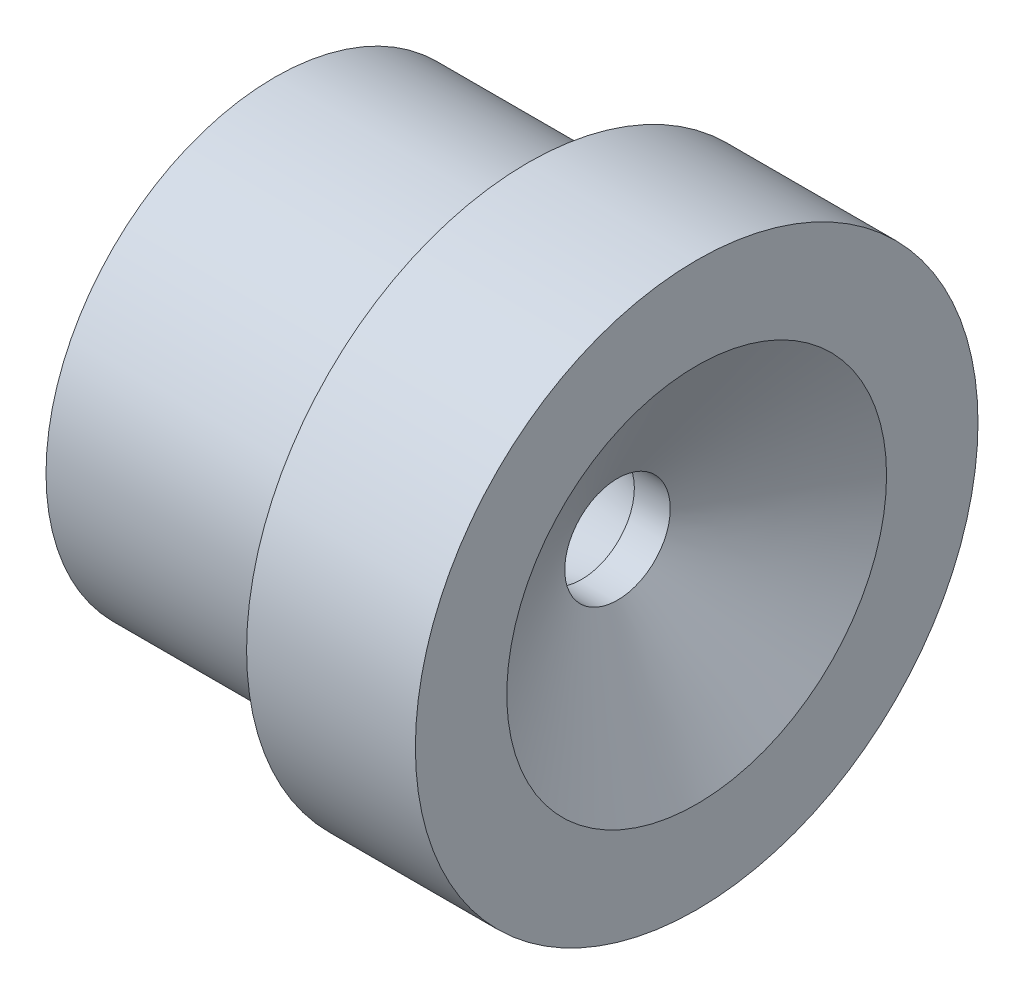
SolidWorks part; units mm, degrees
material "C (Graphite)"
ref_plane "Front Plane" through (0, 0, 0) normal (0, 0, 1) x (1, 0, 0)
ref_plane "Top Plane" through (0, 0, 0) normal (0, 1, 0) x (1, 0, 0)
ref_plane "Right Plane" through (0, 0, 0) normal (1, 0, 0) x (0, 0, -1)
sketch "Sketch1" plane through (0, 0, 0) normal (0, 1, 0) x (1, 0, 0)
  line L0 (0, 0) -> (0, 4.1275)
  line L1 (0, 4.1275) -> (-3.5745, 10.3187)
  line L2 (-3.5745, 10.3187) -> (-5.195, 10.3187)
  line L3 (-5.195, 10.3187) -> (-19.05, 6.6063)
  line L4 (-19.05, 6.6063) -> (-19.05, 2.3749)
  line L5 (-19.05, 2.3749) -> (-7.62, 2.3749)
  line L6 (-7.62, 2.3749) -> (-7.62, 0)
  line L9 (-7.62, 0) -> (0, 0)
  line L10 (5.1187, 12.7) -> (-11.0703, 12.7) construction
  dimension "D1" = 25.4
  dimension "D2" = 4.7625
  dimension "D3" = 60
  dimension "D4" = 15
  dimension "D5" = 17.145
  dimension "D6" = 1.6205
  dimension "D7" = 7.62
  dimension "D8" = 19.05
  dimension "D9" = 20.6502
revolve "Revolve1" add sketch "Sketch1" angle 360 about L10
